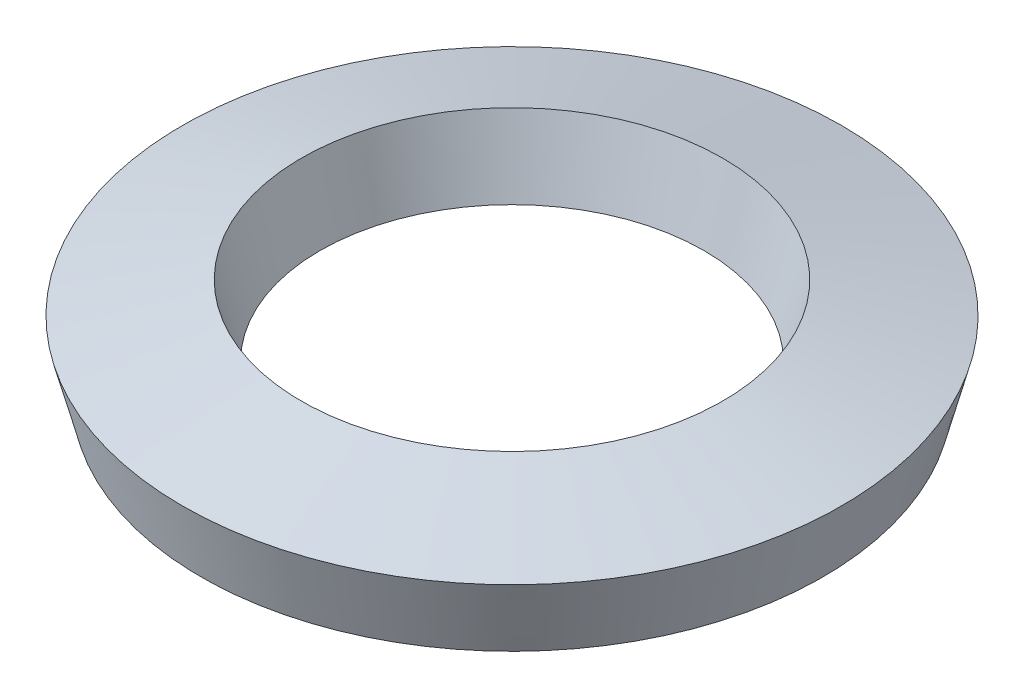
SolidWorks part; units mm, degrees
ref_plane "Front" through (0, 0, 0) normal (0, 0, 1) x (1, 0, 0)
ref_plane "Top" through (0, 0, 0) normal (0, 1, 0) x (1, 0, 0)
ref_plane "Right" through (0, 0, 0) normal (1, 0, 0) x (0, 0, -1)
sketch "Sketch1" plane through (0, 0, 0) normal (0, 0, 1) x (1, 0, 0)
  line L0 (3.559, 0) -> (2.1971, 0.3577)
  line L1 (2.1971, 0.3577) -> (2.41, 1.1684)
  line L2 (2.41, 1.1684) -> (3.7719, 0.8107)
  line L3 (3.7719, 0.8107) -> (3.559, 0)
  line L4 (0, 0) -> (0, 1.1684) construction
  point P5 (2.3036, 0.763)
  dimension "D1" = 1.4081
  dimension "ID" = 4.3942
  dimension "OD" = 7.5438
  dimension "Thickness" = 0.8382
  dimension "Height" = 1.1684
revolve "Revolve1" add sketch "Sketch1" angle 360 about L4
sketch "Sketch15" plane through (0, 0, 0) normal (0, 1, 0) x (1, 0, 0)
  circle A0 centre (0, 0) radius 3.7719
  circle A1 centre (0, 0) radius 2.1971
ref_plane "Plane10" through (0, 1.1684, 0) normal (0, 1, 0) x (-1, 0, 0)
sketch "Sketch13" plane through (0, 1.1684, 0) normal (0, 1, 0) x (-1, 0, 0)
  line L0 (-4.0793, 0.7784) -> (-1.7932, -0.2876)
  line L2 (-3.559, 0) -> (-2.1971, 0) construction
  circle A3 centre (0, 0) radius 1.8161
  circle A4 centre (0, 0) radius 1.8161 construction
  circle A6 centre (0, 0) radius 4.1529
  circle A7 centre (0, 0) radius 4.1529 construction
  dimension "D1" = 25
  dimension "D2" = 0.381
  dimension "D3" = 0.381
  dimension "hex flats" = 14.2748
  dimension "hex flats/2" = 7.366
